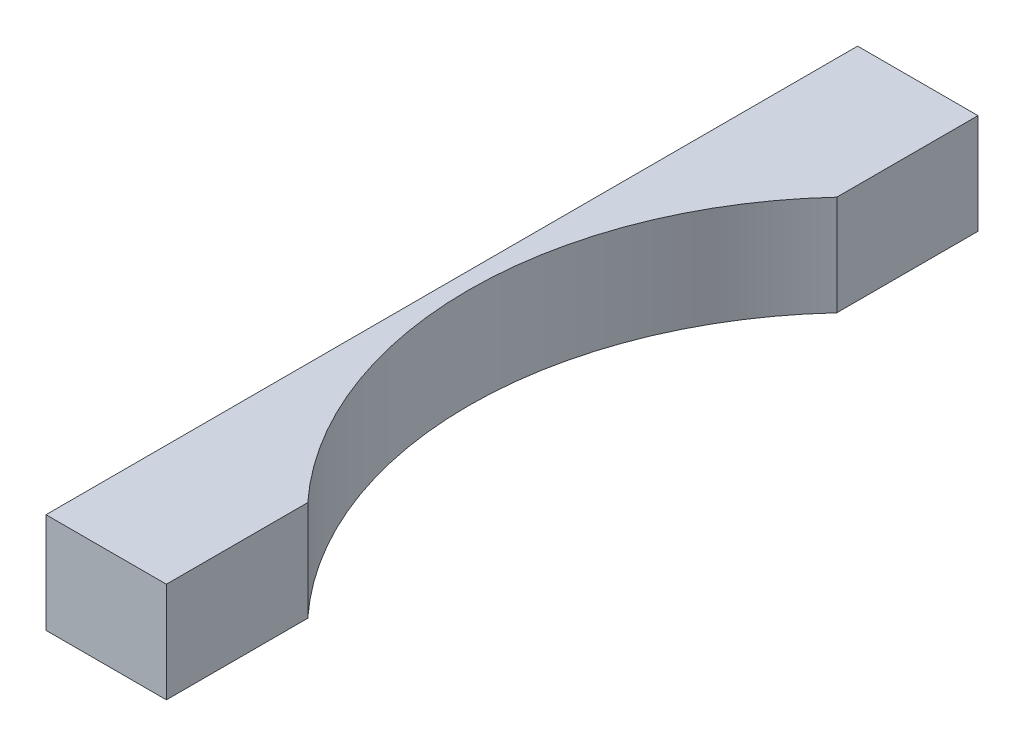
SolidWorks part; units mm, degrees
ref_plane "Płaszczyzna przednia" through (0, 0, 0) normal (0, 0, 1) x (1, 0, 0)
ref_plane "Płaszczyzna górna" through (0, 0, 0) normal (0, 1, 0) x (1, 0, 0)
ref_plane "Płaszczyzna prawa" through (0, 0, 0) normal (1, 0, 0) x (0, 0, -1)
sketch "Sketch1" plane through (0, 0, 0) normal (0, 0, 1) x (1, 0, 0)
  line L1 (-18.6733, 9.9866) -> (5.5367, 9.9866)
  line L2 (-18.6733, 9.9866) -> (-18.6733, 3.9866)
  line L3 (-18.6733, 3.9866) -> (5.5367, 3.9866)
  line L4 (5.5367, 9.9866) -> (5.5367, 3.9866)
  line L5 (-18.6733, 9.9866) -> (5.5367, 3.9866) construction
  line L6 (-18.6733, 3.9866) -> (5.5367, 9.9866) construction
  point P4 (-6.5683, 6.9866)
  dimension "D1" = 24.21
  dimension "D2" = 6
extrude "Boss-Extrude1" add sketch "Sketch1" along normal blind 48.61
sketch "Sketch2" plane through (0, 9.9866, 0) normal (0, 1, 0) x (1, 0, 0)
  line L0 (5.6367, -48.61) -> (-18.5749, -48.61) construction
  line L1 (5.6367, -48.61) -> (-18.5749, -48.61)
  line L2 (5.6367, -48.61) -> (-18.5749, -48.61)
  line L3 (5.6367, -48.61) -> (-18.5749, -48.61)
  line L4 (5.5367, 0) -> (-18.6733, 0)
  line L5 (-18.6733, 0) -> (-18.6733, -48.61)
  line L6 (-18.6733, -48.61) -> (5.5367, -48.61)
  line L7 (5.5367, -48.61) -> (5.5367, 0)
  line L8 (5.5367, 0) -> (-18.6733, 0)
  line L9 (-18.6733, 0) -> (-18.6733, -48.61)
  line L10 (-18.6733, -48.61) -> (5.5367, -48.61)
  line L11 (5.5367, -48.61) -> (5.5367, 0)
  circle A0 centre (5.6367, -24.3) radius 23.31 construction
  circle A1 centre (5.6367, -24.3) radius 23.31
  dimension "D1" = 0
sketch "Sketch3" plane through (0, 9.9866, 0) normal (0, 1, 0) x (1, 0, 0)
  line L0 (-11.4633, 0) -> (-11.4633, -8.4587)
  line L1 (5.5367, 0) -> (-18.6733, 0) construction
  line L2 (5.5367, -48.61) -> (5.5367, 0) construction
  line L3 (5.5367, 0) -> (5.5367, -48.61)
  line L4 (5.5367, 0) -> (-11.4633, 0)
  line L5 (-11.4633, -40.1413) -> (-11.4633, -48.61)
  line L6 (5.6367, -48.61) -> (-18.5749, -48.61) construction
  line L7 (-11.4633, -48.61) -> (5.5367, -48.61)
  circle A0 centre (5.6367, -24.3) radius 23.31 construction
  arc A1 (-11.4633, -8.4587) -> (-11.4633, -40.1413) centre (5.6367, -24.3) ccw
  dimension "D1" = 17
extrude "Cut-Extrude1" cut sketch "Sketch3" against normal through all
